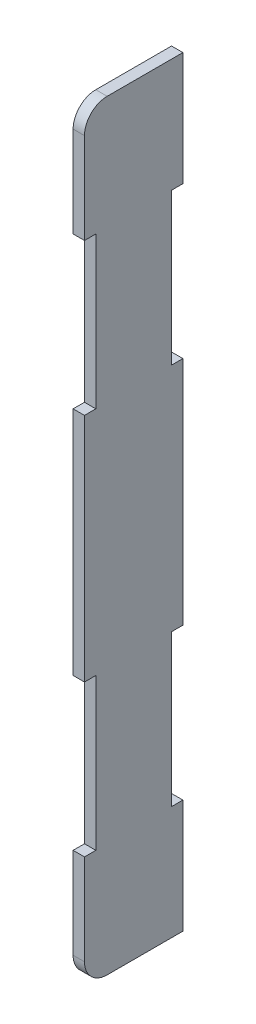
SolidWorks part; units mm, degrees
material "ABS"
ref_plane "前视基准面" through (0, 0, 0) normal (0, 0, 1) x (1, 0, 0)
ref_plane "上视基准面" through (0, 0, 0) normal (0, 1, 0) x (1, 0, 0)
ref_plane "右视基准面" through (0, 0, 0) normal (1, 0, 0) x (0, 0, -1)
sketch "草图1" plane through (0, 0, 0) normal (1, 0, 0) x (0, 0, -1)
  line L1 (-20.4326, 82.399) -> (5.5674, 82.399)
  line L2 (-20.4326, 82.399) -> (-20.4326, -118.601)
  line L3 (-20.4326, -118.601) -> (5.5674, -118.601)
  line L4 (5.5674, 82.399) -> (5.5674, -118.601)
  dimension "D1" = 201
  dimension "D2" = 26
extrude "凸台-拉伸1" add sketch "草图1" along normal blind 3
sketch "草图2" plane through (0, 0, 0) normal (1, 0, 0) x (0, 0, -1)
  line L0 (5.5674, -118.601) -> (5.5674, 82.399) construction
  line L1 (2.5674, -88.601) -> (5.5674, -88.601)
  line L2 (2.5674, -88.601) -> (2.5674, -48.601)
  line L3 (2.5674, -48.601) -> (5.5674, -48.601)
  line L4 (5.5674, -88.601) -> (5.5674, -48.601)
  line L5 (-20.4326, -118.601) -> (5.5674, -118.601) construction
  line L6 (-20.4326, -18.101) -> (5.5674, -18.101) construction
  line L7 (-17.4326, -88.601) -> (-20.4326, -88.601)
  line L8 (-20.4326, -88.601) -> (-20.4326, -48.601)
  line L9 (-17.4326, -48.601) -> (-20.4326, -48.601)
  line L10 (-17.4326, -88.601) -> (-17.4326, -48.601)
  line L11 (-7.4326, 82.399) -> (-7.4326, -118.601) construction
  line L12 (5.5674, 82.399) -> (-20.4326, 82.399) construction
  line L13 (-17.4326, 12.399) -> (-20.4326, 12.399)
  line L14 (-20.4326, 52.399) -> (-20.4326, 12.399)
  line L15 (-17.4326, 52.399) -> (-17.4326, 12.399)
  line L16 (-17.4326, 52.399) -> (-20.4326, 52.399)
  line L17 (2.5674, 52.399) -> (5.5674, 52.399)
  line L18 (2.5674, 12.399) -> (5.5674, 12.399)
  line L19 (5.5674, 52.399) -> (5.5674, 12.399)
  line L20 (2.5674, 52.399) -> (2.5674, 12.399)
  line L21 (-20.4326, 82.399) -> (-20.4326, -118.601) construction
  line L23 (5.5674, 82.399) -> (-20.4326, 82.399) construction
  line L24 (-20.4326, -118.601) -> (5.5674, -118.601) construction
  dimension "D1" = 40
  dimension "D2" = 30
  dimension "D3" = 3
  dimension "D4" = 30.5
  dimension "D5" = 100.5
  dimension "D6" = 100.5
extrude "切除-拉伸1" cut sketch "草图2" along normal blind 3
fillet "圆角2" radius 6 1 edges at (1.5, -118.601, 20.4326)
fillet "圆角3" radius 6 1 edges at (1.5, 82.399, 20.4326)
